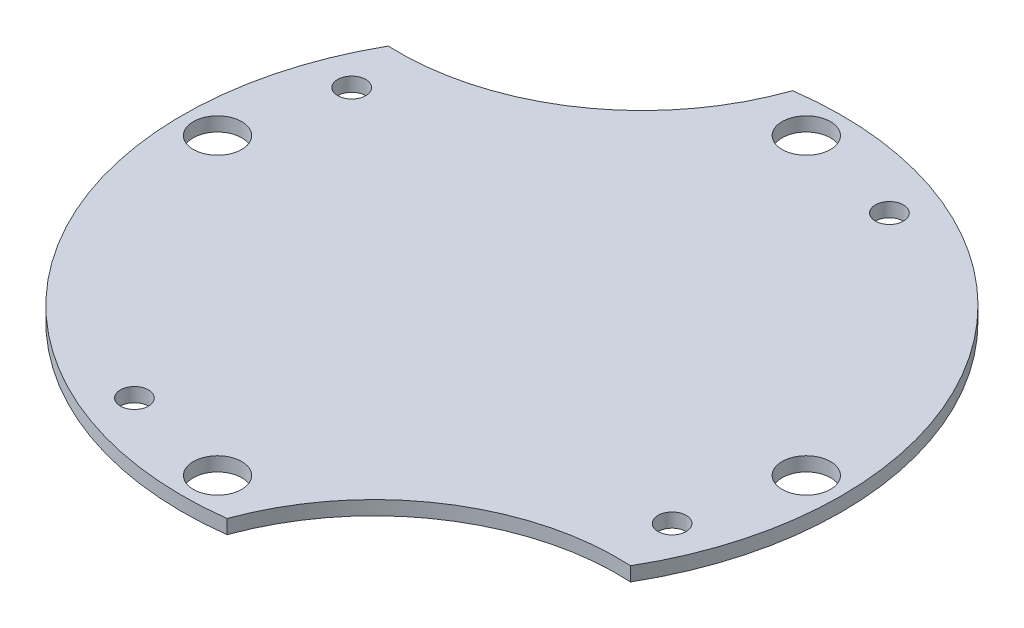
SolidWorks part; units mm, degrees
ref_plane "Front Plane" through (0, 0, 0) normal (0, 0, 1) x (1, 0, 0)
ref_plane "Top Plane" through (0, 0, 0) normal (0, 1, 0) x (1, 0, 0)
ref_plane "Right Plane" through (0, 0, 0) normal (1, 0, 0) x (0, 0, -1)
sketch "Sketch1" plane through (0, 0, 0) normal (0, 1, 0) x (1, 0, 0)
  circle A4 centre (9.0351, 0.4961) radius 37.5
  dimension "D1" = 75
extrude "Boss-Extrude1" add sketch "Sketch1" along normal blind 1.6
sketch "Sketch3" plane through (0, 1.6, 0) normal (0, 1, 0) x (1, 0, 0)
  line L0 (9.0351, 0.5024) -> (9.0351, 33.991) construction
  line L1 (-30.8505, 0.5024) -> (49.1495, 0.5024) construction
  line L2 (9.0351, 0.5024) -> (-15.2278, 23.4731) construction
  line L3 (9.0351, 0.5024) -> (-3.3269, -30.0947) construction
  circle A11 centre (-3.3269, -30.0947) radius 1.6
  circle A19 centre (-24.4598, 0.4961) radius 2.75
  circle A20 centre (9.0351, 33.991) radius 2.75
  circle A21 centre (42.53, 0.4961) radius 2.75
  circle A22 centre (9.0351, -32.9988) radius 2.75
  circle A23 centre (-21.5557, 12.8581) radius 1.6
  circle A24 centre (21.3971, 31.0869) radius 1.6
  circle A25 centre (39.6259, -11.8659) radius 1.6
  point P13 (9.1495, 0.5024)
  point P16 (9.0351, 0.4961)
  point P25 (9.0351, 0.4961)
  point P26 (9.0351, 0.4961)
  point P29 (9.1495, 0.5024)
  point P30 (9.0351, 0.4961)
  point P31 (9.1495, 0.5024)
  dimension "D1" = 3.2
  dimension "D3" = 4
  dimension "D4" = 68
  dimension "D6" = 33
  dimension "D2" = 5.5
  dimension "D5" = 4
sketch "Sketch5" plane through (0, 1.6, 0) normal (0, 1, 0) x (1, 0, 0)
  line L0 (9.1495, 0.5024) -> (-10.6257, 20.2776) construction
  line L1 (9.1495, 0.5024) -> (9.1495, 40.5024) construction
  line L2 (9.1495, 0.5024) -> (9.1495, 213.1036) construction
  line L3 (-3.4124, 24.378) -> (15.8961, 5.0695) construction
  line L4 (9.1495, 0.5024) -> (-0.0186, -8.6657) construction
  point P7 (-0.7381, 10.39)
  dimension "D1" = 45
  dimension "D2" = 8
extrude "Cut-Extrude1" cut sketch "Sketch3" against normal blind 10
sketch "Sketch6" plane through (0, 1.6, 0) normal (0, 1, 0) x (1, 0, 0)
  line L0 (-9.32, 27.8537) -> (-15.5103, 36.8143) construction
  line L1 (-15.5103, 36.8143) -> (-24.9582, 50.4907) construction
  line L2 (9.0351, 0.4961) -> (9.0351, 24.2394) construction
  line L3 (9.0351, 0.4961) -> (28.1738, 0.4961) construction
  line L4 (9.0351, 0.4961) -> (-9.32, 27.8537) construction
  line L5 (9.0351, 0.4961) -> (-19.7142, -18.7928) construction
  line L6 (9.0351, 0.4961) -> (-11.6068, 0.4961) construction
  circle A0 centre (39.9126, -46.0852) radius 27.7299
  circle A1 centre (-22.3602, 46.7299) radius 27.7299
  dimension "D1" = 90
extrude "Cut-Extrude2" cut sketch "Sketch6" against normal blind 10
sketch "Sketch7" plane through (0, 1.6, 0) normal (0, 1, 0) x (1, 0, 0)
  line L0 (9.0351, 0.4961) -> (9.0351, 19.18) construction
  line L1 (9.0351, 0.4961) -> (-5.9574, 22.841) construction
  dimension "D1" = 33.86
